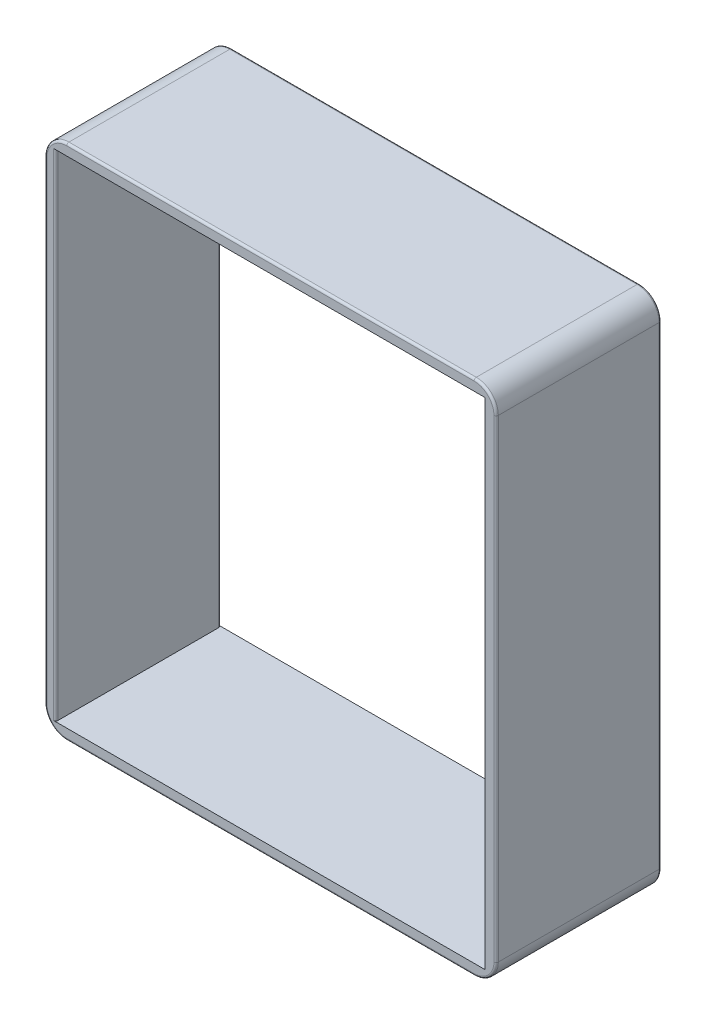
SolidWorks part; units mm, degrees
ref_plane "Front Plane" through (0, 0, 0) normal (0, 0, 1) x (1, 0, 0)
ref_plane "Top Plane" through (0, 0, 0) normal (0, 1, 0) x (1, 0, 0)
ref_plane "Right Plane" through (0, 0, 0) normal (1, 0, 0) x (0, 0, -1)
sketch "Sketch1" plane through (0, 0, 0) normal (0, 0, 1) x (1, 0, 0)
  line L0 (-20.5, -23.5) -> (-20.5, 23.5)
  line L1 (-19.5, -22.5) -> (19.5, -22.5)
  line L2 (-19.5, -22.5) -> (-19.5, 22.5)
  line L3 (-19.5, 22.5) -> (19.5, 22.5)
  line L4 (19.5, -22.5) -> (19.5, 22.5)
  line L5 (-19.5, -22.5) -> (19.5, 22.5) construction
  line L6 (-19.5, 22.5) -> (19.5, -22.5) construction
  line L7 (-20.5, 23.5) -> (20.5, 23.5)
  line L8 (20.5, -23.5) -> (20.5, 23.5)
  line L9 (-20.5, -23.5) -> (20.5, -23.5)
  point P0 (0, 0)
  dimension "D1" = 39
  dimension "D2" = 45
  dimension "D3" = 1
extrude "Boss-Extrude1" add sketch "Sketch1" along normal blind 15
fillet "Fillet1" radius 2 4 edges at (-20.5, -23.5, 7.5) (20.5, -23.5, 7.5) (20.5, 23.5, 7.5) (-20.5, 23.5, 7.5)
fillet "Fillet4" radius 0.2 18 edges at (-19.9142, 22.9142, 15) (0, 23.5, 15) (19.9142, 22.9142, 15) (20.5, 0, 15) (19.9142, -22.9142, 15) (0, -23.5, 15) (-19.9142, -22.9142, 15) (-19.9142, 22.9142, 0) (0, 23.5, 0) (19.9142, 22.9142, 0) (20.5, 0, 0) (19.9142, -22.9142, 0) (0, -23.5, 0) (-19.9142, -22.9142, 0) (-20.5, 0, 15) (-20.5, 0, 0) (-19.5, 0, 0) (-19.5, 0, 15)
